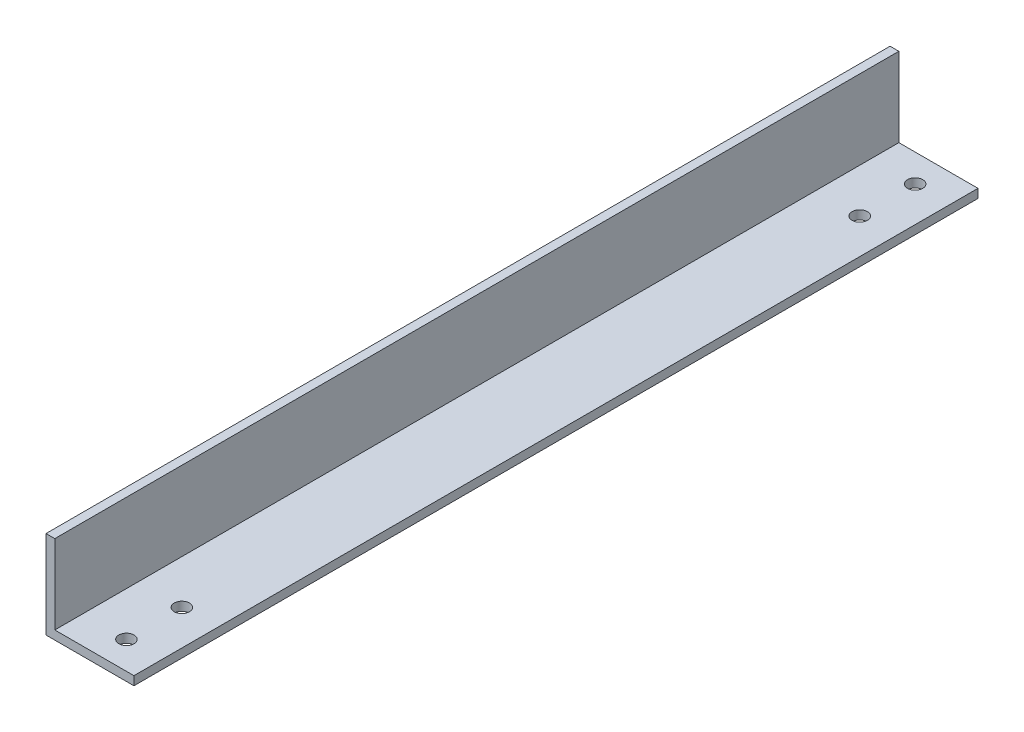
SolidWorks part; units mm, degrees
ref_plane "Front Plane" through (0, 0, 0) normal (0, 0, 1) x (1, 0, 0)
ref_plane "Top Plane" through (0, 0, 0) normal (0, 1, 0) x (1, 0, 0)
ref_plane "Right Plane" through (0, 0, 0) normal (1, 0, 0) x (0, 0, -1)
sketch "Sketch1" plane through (0, 0, 0) normal (0, 0, 1) x (1, 0, 0)
  line L0 (0, 0) -> (0, 31.75)
  line L1 (0, 31.75) -> (3.175, 31.75)
  line L2 (3.175, 31.75) -> (3.175, 3.175)
  line L3 (3.175, 3.175) -> (31.75, 3.175)
  line L4 (31.75, 3.175) -> (31.75, 0)
  line L5 (31.75, 0) -> (0, 0)
  dimension "D1" = 31.75
  dimension "D2" = 31.75
  dimension "D3" = 28.575
  dimension "D4" = 28.575
extrude "Boss-Extrude1" add sketch "Sketch1" along normal blind 304.8
hole_wizard "M5 Clearance Hole1" positions "Sketch2" profile "Sketch3" hole size "M5" standard "ANSI Metric"
sketch "Sketch2" plane through (0, 3.175, 0) normal (0, 1, 0) x (1, 0, 0)
  line L0 (31.75, -304.8) -> (31.75, 0) construction
  line L1 (31.75, -304.8) -> (3.175, -304.8) construction
  line L2 (31.75, 0) -> (3.175, 0) construction
  point P0 (19.05, -10)
  point P2 (19.05, -294.8)
  point P11 (19.05, -30)
  point P13 (19.05, -274.8)
  point P16 (0, 0)
  point P17 (0, 0)
  dimension "D1" = 12.7
  dimension "D2" = 12.7
  dimension "D3" = 10
  dimension "D4" = 10
  dimension "D5" = 20
  dimension "D6" = 20
sketch "Sketch3" plane through (19.05, 3.175, 10) normal (1, 0, 0) x (0, 0, 1)
  line L0 (0, 0) -> (0, 27.0524)
  line L1 (0, 27.0524) -> (2.75, 25.4)
  line L2 (2.75, 25.4) -> (2.75, 0)
  line L5 (2.75, 0) -> (0, 0)
  line L10 (0, 27.0524) -> (-2.75, 25.4) construction
  line L11 (0, -6.35) -> (0, 107.95) construction
  dimension "Hole Dia." = 5.5
  dimension "Hole Depth" = 25.4
  dimension "Drill Angle" = 118
